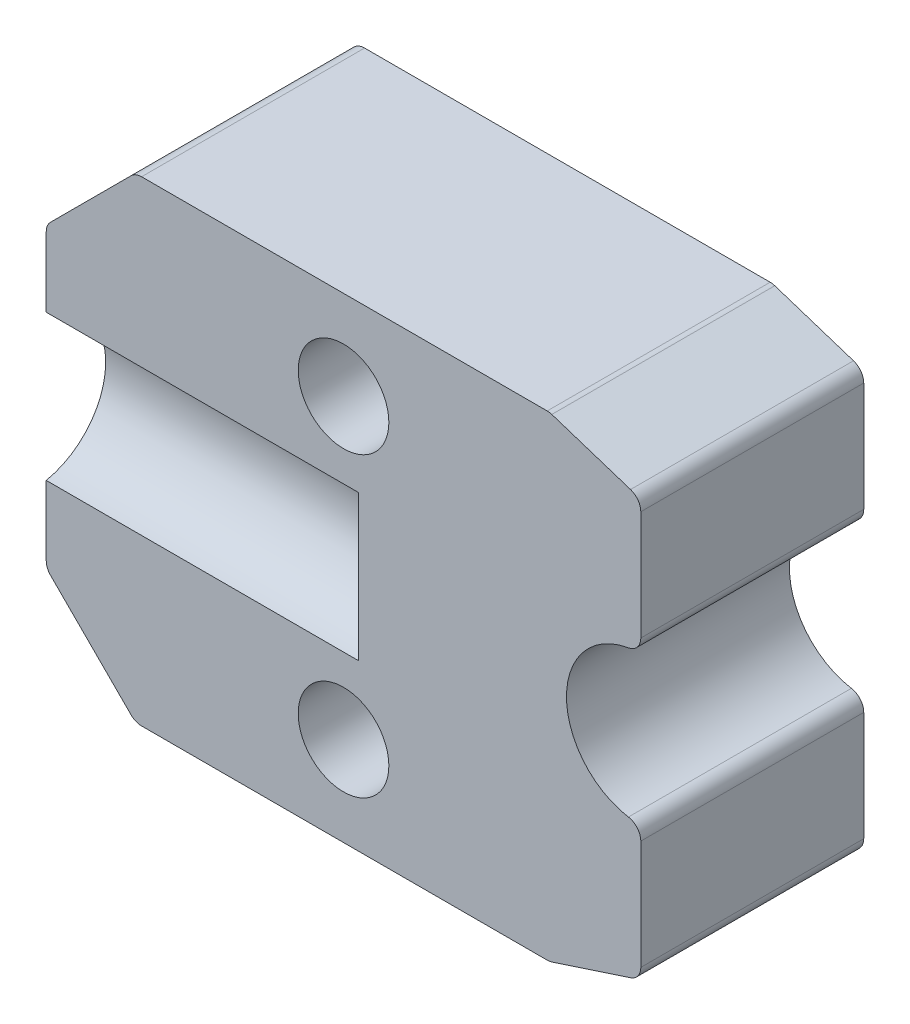
SolidWorks part; units mm, degrees
ref_plane "前视基准面" through (0, 0, 0) normal (0, 0, 1) x (1, 0, 0)
ref_plane "上视基准面" through (0, 0, 0) normal (0, 1, 0) x (1, 0, 0)
ref_plane "右视基准面" through (0, 0, 0) normal (1, 0, 0) x (0, 0, -1)
sketch "草图1" plane through (0, 0, 0) normal (0, 0, 1) x (1, 0, 0)
  line L0 (0, -5) -> (0, 5) construction
  line L1 (-10, 8) -> (-10, -8)
  line L2 (-10, -8) -> (6.9314, -8)
  line L3 (6.9314, -8) -> (10, -7)
  line L4 (10, -7) -> (10, 7)
  line L5 (10, 7) -> (6.9314, 8)
  line L6 (6.9314, 8) -> (-10, 8)
  circle A0 centre (0, 5) radius 1.525
  circle A1 centre (0, -5) radius 1.525
  point P4 (0, 0)
  point P7 (10, 0)
  dimension "D1" = 3.05
  dimension "D2" = 10
  dimension "D3" = 3
  dimension "D4" = 3
  dimension "D5" = 10
  dimension "D6" = 14
  dimension "D7" = 20
  dimension "D8" = 5
extrude "凸台-拉伸1" add sketch "草图1" along normal mid plane 7.5
sketch "草图2" plane through (-10, 0, 0) normal (-1, 0, 0) x (0, 0, 1)
  line L0 (3.75, 8) -> (3.75, -8) construction
  circle A0 centre (4.25, 0) radius 2.5
  dimension "D1" = 0.5
  dimension "D2" = 5
extrude "切除-拉伸1" cut sketch "草图2" against normal blind 10.5
chamfer "倒角1" distance 3 angle 45 2 edges at (-10, -8, 0) (-10, 8, 0)
sketch "草图3" plane through (0, 0, -3.75) normal (0, 0, -1) x (-1, 0, 0)
  line L0 (-10, -7) -> (-10, 7) construction
  circle A0 centre (-10, 0) radius 2.5
  dimension "D1" = 5
extrude "切除-拉伸2" cut sketch "草图3" against normal through all
fillet "圆角1" radius 0.5 10 edges at (10, 7, 0) (6.9314, 8, 0) (-7, 8, 0) (-10, 5, 0) (-10, -5, 0) (-7, -8, 0) (6.9314, -8, 0) (10, -7, 0) (10, -2.5, 0) (10, 2.5, 0)
